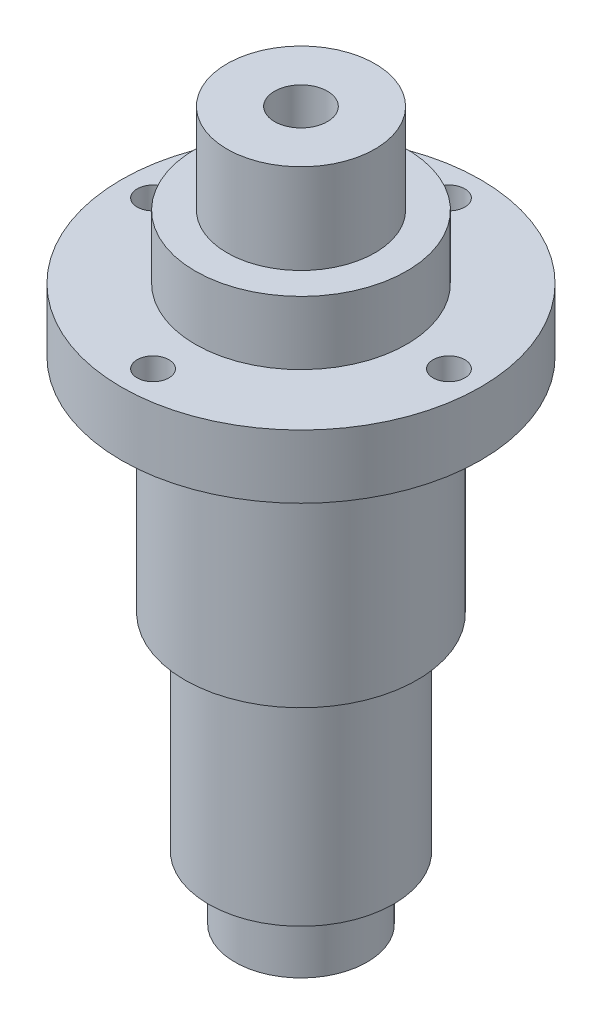
SolidWorks part; units mm, degrees
material "合金钢 (SS)"
ref_plane "前视基准面" through (0, 0, 0) normal (0, 0, 1) x (1, 0, 0)
ref_plane "上视基准面" through (0, 0, 0) normal (0, 1, 0) x (1, 0, 0)
ref_plane "右视基准面" through (0, 0, 0) normal (1, 0, 0) x (0, 0, -1)
sketch "草图1" plane through (0, 0, 0) normal (0, 1, 0) x (1, 0, 0)
  circle A12 centre (0, 0) radius 20
extrude "凸台-拉伸1" add sketch "草图1" along normal blind 12
sketch "草图3" plane through (0, 0, 0) normal (0, -1, 0) x (1, 0, 0)
  circle A0 centre (0, 0) radius 34
extrude "凸台-拉伸2" add sketch "草图3" along normal blind 12
sketch "草图4" plane through (0, -12, 0) normal (0, -1, 0) x (1, 0, 0)
  circle A0 centre (0, 0) radius 22
extrude "凸台-拉伸3" add sketch "草图4" along normal blind 42
sketch "草图5" plane through (0, -54, 0) normal (0, -1, 0) x (1, 0, 0)
  circle A0 centre (0, 0) radius 17.5
extrude "凸台-拉伸5" add sketch "草图5" along normal blind 39 contours A0
sketch "草图6" plane through (0, -93, 0) normal (0, -1, 0) x (1, 0, 0)
  circle A0 centre (0, 0) radius 12.5
extrude "凸台-拉伸6" add sketch "草图6" along normal blind 12
sketch "草图8" plane through (0, -12, 0) normal (0, -1, 0) x (1, 0, 0)
  circle A0 centre (0, 0) radius 16
  circle A1 centre (0, 0) radius 10
extrude "凸台-拉伸7" add sketch "草图8" along normal blind 18
sketch "草图11" plane through (0, -12, 0) normal (0, -1, 0) x (1, 0, 0)
  circle A0 centre (0, 28) radius 3
extrude "切除-拉伸9" cut sketch "草图11" against normal blind 12 contours A0
pattern_circular "阵列(圆周)1" count 4 over 360 about axis through (0, 0, 0) along (0, 1, 0) of "切除-拉伸9"
sketch "草图12" plane through (0, 12, 0) normal (0, 1, 0) x (1, 0, 0)
  circle A0 centre (0, 0) radius 14
extrude "凸台-拉伸8" add sketch "草图12" along normal blind 17 contours A0
sketch "草图14" plane through (0, 29, 0) normal (0, 1, 0) x (1, 0, 0)
  circle A0 centre (0, 0) radius 5
extrude "切除-拉伸10" cut sketch "草图14" against normal blind 15
